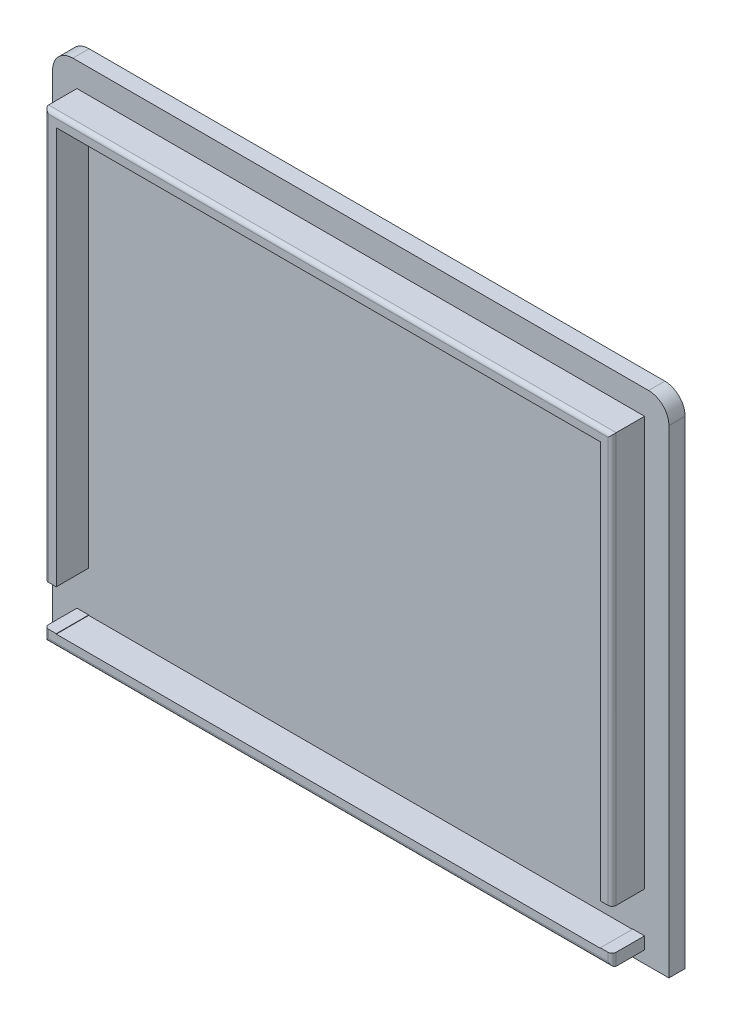
SolidWorks part; units mm, degrees
ref_plane "Front Plane" through (0, 0, 0) normal (0, 0, 1) x (1, 0, 0)
ref_plane "Top Plane" through (0, 0, 0) normal (0, 1, 0) x (1, 0, 0)
ref_plane "Right Plane" through (0, 0, 0) normal (1, 0, 0) x (0, 0, -1)
sketch "Sketch1" plane through (0, 0, 0) normal (0, 0, 1) x (1, 0, 0)
  line L1 (-67.075, 54.075) -> (67.075, 54.075)
  line L2 (-67.075, 54.075) -> (-67.075, -54.075)
  line L3 (-67.075, -54.075) -> (67.075, -54.075)
  line L4 (67.075, 54.075) -> (67.075, -54.075)
  line L5 (-67.075, 54.075) -> (67.075, -54.075) construction
  line L6 (-67.075, -54.075) -> (67.075, 54.075) construction
  line L7 (-69.975, 56.975) -> (69.975, 56.975)
  line L8 (-69.975, 56.975) -> (-69.975, -56.975)
  line L9 (-69.975, -56.975) -> (69.975, -56.975)
  line L10 (69.975, 56.975) -> (69.975, -56.975)
  line L11 (-69.975, 56.975) -> (69.975, -56.975) construction
  line L12 (-69.975, -56.975) -> (69.975, 56.975) construction
  point P0 (0, 0)
  point P6 (0, 0)
  dimension "D1" = 139.95
  dimension "D2" = 113.95
  dimension "D3" = 2.9
  dimension "D4" = 2.9
extrude "Boss-Extrude1" add sketch "Sketch1" along normal blind 8
sketch "Sketch2" plane through (0, 0, 0) normal (0, 0, -1) x (-1, 0, 0)
  line L9 (75.975, 62.975) -> (75.975, -56.975)
  line L10 (-75.975, 62.975) -> (75.975, 62.975)
  line L11 (-75.975, -56.975) -> (-75.975, 62.975)
  line L12 (75.975, 62.975) -> (75.975, -56.975)
  line L13 (-75.975, 62.975) -> (75.975, 62.975)
  line L14 (-75.975, -56.975) -> (-75.975, 62.975)
  line L21 (-75.975, -59.975) -> (75.975, -59.975)
  line L22 (75.975, -59.975) -> (75.975, -56.975)
  line L23 (-75.975, -59.975) -> (-75.975, -56.975)
  line L24 (69.975, -56.975) -> (-69.975, -56.975) construction
  dimension "D2" = 3
  dimension "D1" = 6
extrude "Boss-Extrude3" add sketch "Sketch2" along normal blind 4
fillet "Fillet1" radius 5 2 edges at (-75.975, 62.975, -2) (75.975, 62.975, -2)
fillet "Fillet2" radius 1 4 edges at (69.975, 0, 8) (0, -56.975, 8) (-69.975, 0, 8) (0, 56.975, 8)
sketch "Sketch3" plane through (0, 0, 8) normal (0, 0, 1) x (1, 0, 0)
  line L0 (69.975, -56.975) -> (69.975, 56.975) construction
  line L1 (69.975, -53.975) -> (67.075, -53.975)
  line L2 (69.975, -53.975) -> (69.975, -43.975)
  line L3 (69.975, -43.975) -> (67.075, -43.975)
  line L4 (67.075, -53.975) -> (67.075, -43.975)
  line L5 (67.075, -54.075) -> (67.075, 54.075) construction
  line L6 (-69.975, -56.975) -> (69.975, -56.975) construction
  line L7 (0, 0) -> (0, -10.7665) construction
  line L8 (-69.975, -43.975) -> (-67.075, -43.975)
  line L9 (-67.075, -53.975) -> (-67.075, -43.975)
  line L10 (-69.975, -53.975) -> (-67.075, -53.975)
  line L11 (-69.975, -53.975) -> (-69.975, -43.975)
  dimension "D1" = 10
  dimension "D2" = 3
extrude "Cut-Extrude1" cut sketch "Sketch3" against normal up to surface (8 mm away) up to face at (0, 20.6702, 0)
sketch "Sketch4" plane through (0, 0, -4) normal (0, 0, -1) x (-1, 0, 0)
  line L0 (70.975, -52.975) -> (-93.9545, -52.975) construction
  line L1 (-75.975, -59.975) -> (75.975, -59.975) construction
  line L2 (75.975, -59.975) -> (75.975, 57.975) construction
  text T0 "<i>BSD</i>" font "Century Gothic" height 5
  dimension "D1" = 7
  dimension "D2" = 5
sketch "Sketch5" plane through (0, 0, -4) normal (0, 0, -1) x (-1, 0, 0)
  line L0 (-1000, 0) -> (49000, 0) construction
  line L1 (0, -1000) -> (0, 49000) construction
  line L2 (-8, -39.975) -> (8, -39.975)
  line L3 (-8, -9.975) -> (8, -9.975)
  line L6 (-75.975, -59.975) -> (75.975, -59.975) construction
  arc A0 (-8, -9.975) -> (-8, -39.975) centre (-44, -24.975) cw
  arc A1 (8, -9.975) -> (8, -39.975) centre (44, -24.975) ccw
  arc A3 (6.8182, 16.6641) -> (-6.8182, 16.6641) centre (0, 30.025) ccw
  arc A4 (-6.8182, 16.6641) -> (0, 5.5301) centre (-12.5, 5.5301) ccw
  arc A6 (6.8182, 16.6641) -> (0, 5.5301) centre (12.5, 5.5301) cw
  point P8 (-5, -24.975)
  point P20 (0, 40.025)
  dimension "D3" = 3
  dimension "D5" = 30
  dimension "D6" = 40
  dimension "D7" = 25
  dimension "D1" = 30
  dimension "D2" = 5
  dimension "D4" = 3
  dimension "D8" = 20
extrude "Cut-Extrude4" cut sketch "Sketch5" against normal blind 3
extrude "Cut-Extrude5" cut sketch "Sketch4" against normal blind 3
